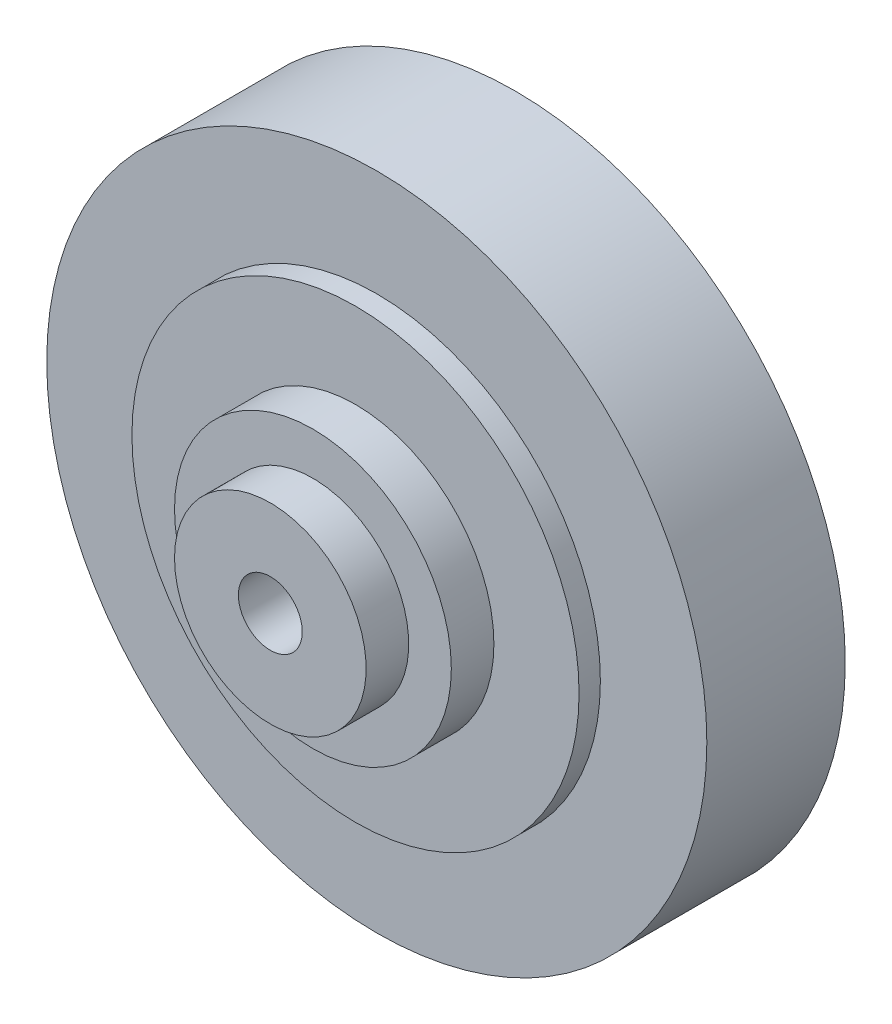
SolidWorks part; units mm, degrees
ref_plane "Alzado" through (0, 0, 0) normal (0, 0, 1) x (1, 0, 0)
ref_plane "Planta" through (0, 0, 0) normal (0, 1, 0) x (1, 0, 0)
ref_plane "Vista lateral" through (0, 0, 0) normal (1, 0, 0) x (0, 0, -1)
sketch "Croquis1" plane through (0, 0, 0) normal (1, 0, 0) x (0, 0, -1)
  line L0 (0, 0) -> (2, 0) construction
  line L1 (2, 0) -> (2, 3) construction
  line L2 (2, 3) -> (2, 10) construction
  line L3 (2, 10) -> (-11, 10) construction
  line L4 (-11, 10) -> (-11, 27) construction
  line L5 (-11, 27) -> (0, 30) construction
  line L6 (0, 30) -> (0, 31) construction
  line L7 (0, 31) -> (-13, 31) construction
  line L8 (-13, 31) -> (-13, 21) construction
  line L9 (-13, 21) -> (-15, 21) construction
  line L10 (-15, 21) -> (-15, 13) construction
  line L11 (-15, 13) -> (-19, 13) construction
  line L12 (-19, 13) -> (-19, 9) construction
  line L13 (-19, 9) -> (-23, 9) construction
  line L14 (-23, 9) -> (-23, 3) construction
  line L15 (-23, 3) -> (2, 3) construction
  line L16 (0, 0) -> (-34.1222, 0) construction
  line L17 (2, 3) -> (-23, 3)
  line L18 (-23, 3) -> (-23, 9)
  line L19 (-23, 9) -> (-19, 9)
  line L20 (-19, 9) -> (-19, 13)
  line L21 (-19, 13) -> (-15, 13)
  line L22 (-15, 13) -> (-15, 21)
  line L23 (-15, 21) -> (-13, 21)
  line L24 (-13, 21) -> (-13, 31)
  line L25 (-13, 31) -> (0, 31)
  line L26 (0, 31) -> (0, 30)
  line L27 (0, 30) -> (-11, 27)
  line L28 (-11, 27) -> (-11, 10)
  line L29 (-11, 10) -> (2, 10)
  line L30 (2, 10) -> (2, 3)
  dimension "D1" = 0
  dimension "D2" = 25
  dimension "D3" = 13
  dimension "D4" = 11
  dimension "D5" = 1
  dimension "D7" = 28
  dimension "D8" = 7
  dimension "D9" = 17
  dimension "D10" = 6
  dimension "D11" = 4
  dimension "D12" = 8
  dimension "D13" = 4
  dimension "D14" = 4
  dimension "D15" = 2
revolve "Revolución1" add sketch "Croquis1" angle 360 about L16
